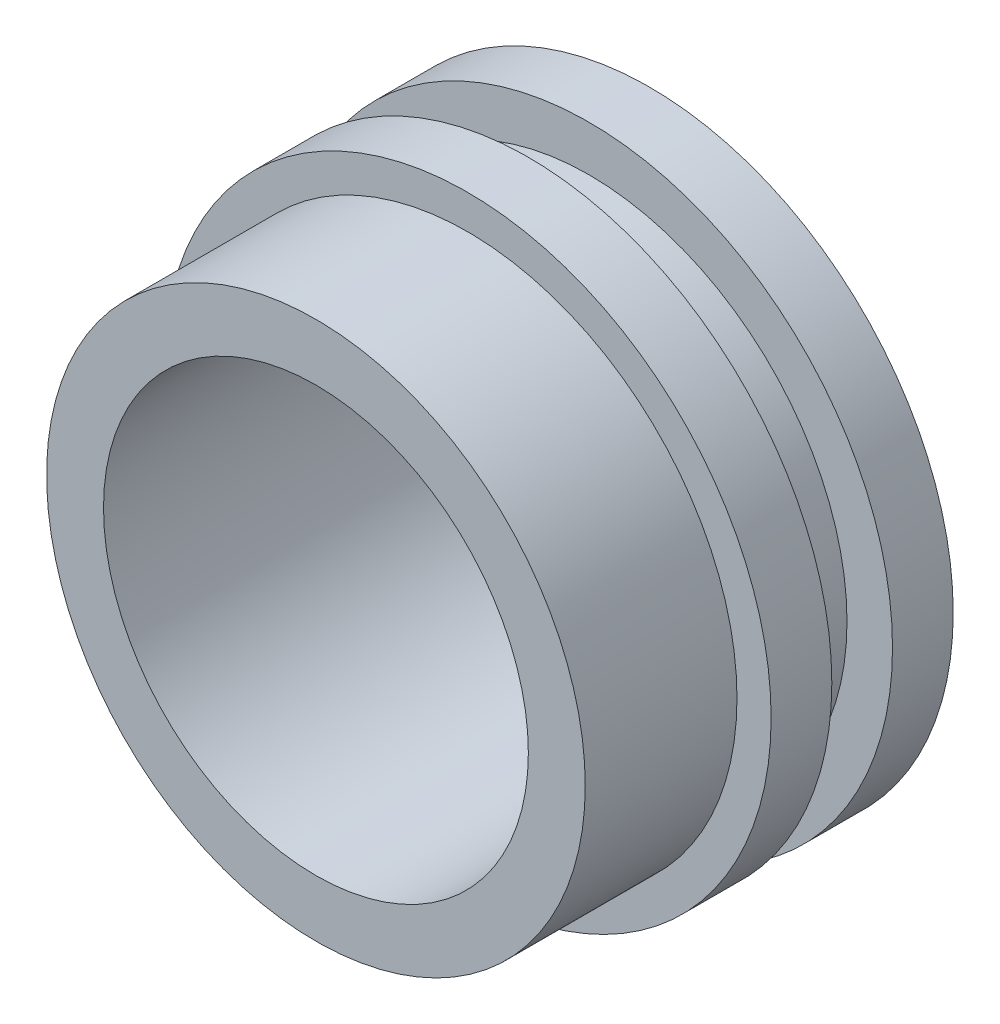
SolidWorks part; units mm, degrees
material "ABS"
ref_plane "Front Plane" through (0, 0, 0) normal (0, 0, 1) x (1, 0, 0)
ref_plane "Top Plane" through (0, 0, 0) normal (0, 1, 0) x (1, 0, 0)
ref_plane "Right Plane" through (0, 0, 0) normal (1, 0, 0) x (0, 0, -1)
sketch "Sketch1" plane through (0, 0, 0) normal (0, 0, 1) x (1, 0, 0)
  circle A0 centre (0, 0) radius 10
extrude "Boss-Extrude1" add sketch "Sketch1" along normal blind 2
sketch "Sketch2" plane through (0, 0, 0) normal (0, 0, 1) x (1, 0, 0)
  circle A0 centre (0, 0) radius 8.5
  dimension "D1" = 17
extrude "Boss-Extrude2" add sketch "Sketch2" along normal blind 6
sketch "Sketch3" plane through (0, 0, 0) normal (0, 0, 1) x (1, 0, 0)
  circle A0 centre (0, 0) radius 10
extrude "Boss-Extrude3" add sketch "Sketch3" along normal blind 2 from offset 4
sketch "Sketch5" plane through (0, 0, 0) normal (0, 0, 1) x (1, 0, 0)
  circle A0 centre (0, 0) radius 7
extrude "Cut-Extrude2" cut sketch "Sketch5" along normal through all
sketch "Sketch6" plane through (0, 0, 0) normal (0, 0, 1) x (1, 0, 0)
  circle A0 centre (0, 0) radius 7
  circle A1 centre (0, 0) radius 8.875
  dimension "D1" = 17.75
extrude "Boss-Extrude4" add sketch "Sketch6" along normal blind 5 from surface at 6 starting at face at (10, 0, 6)
